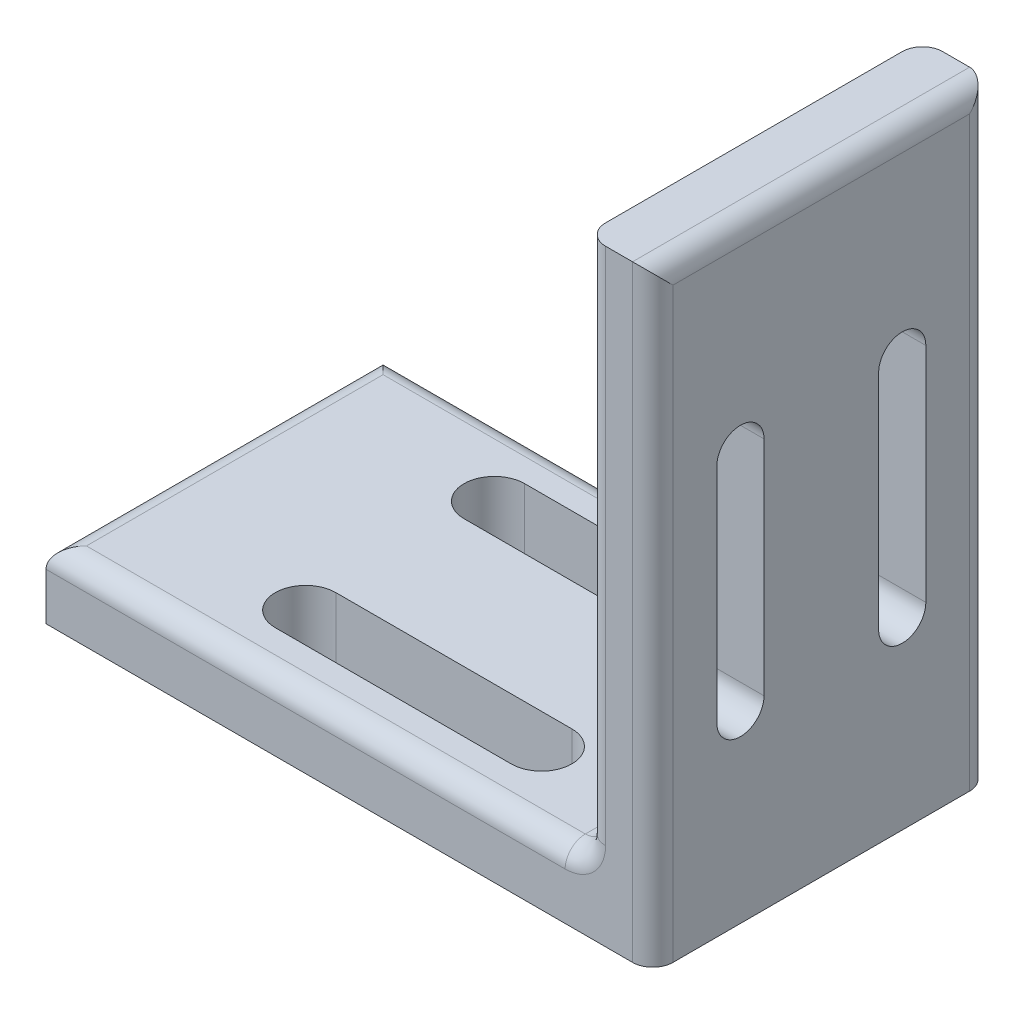
SolidWorks part; units mm, degrees
material "ABS"
ref_plane "Front Plane" through (0, 0, 0) normal (0, 0, 1) x (1, 0, 0)
ref_plane "Top Plane" through (0, 0, 0) normal (0, 1, 0) x (1, 0, 0)
ref_plane "Right Plane" through (0, 0, 0) normal (1, 0, 0) x (0, 0, -1)
sketch "Sketch2" plane through (0, 0, 0) normal (0, 1, 0) x (1, 0, 0)
  line L1 (-22.5, 12.5) -> (22.5, 12.5)
  line L2 (-22.5, 12.5) -> (-22.5, -12.5)
  line L3 (-22.5, -12.5) -> (22.5, -12.5)
  line L4 (22.5, 12.5) -> (22.5, -12.5)
  line L5 (-22.5, 12.5) -> (22.5, -12.5) construction
  line L6 (-22.5, -12.5) -> (22.5, 12.5) construction
  point P0 (0, 0)
  dimension "D1" = 45
  dimension "D2" = 25
extrude "Boss-Extrude1" add sketch "Sketch2" along normal blind 5
sketch "Sketch3" plane through (0, 5, 0) normal (0, 1, 0) x (1, 0, 0)
  line L0 (-8.75, 7) -> (8.75, 7) construction
  line L1 (-8.75, 9.25) -> (8.75, 9.25)
  line L2 (-8.75, 4.75) -> (8.75, 4.75)
  line L3 (-8.75, -7) -> (8.75, -7) construction
  line L4 (-8.75, -4.75) -> (8.75, -4.75)
  line L5 (-8.75, -9.25) -> (8.75, -9.25)
  arc A0 (-8.75, 9.25) -> (-8.75, 4.75) centre (-8.75, 7) ccw
  arc A1 (8.75, 4.75) -> (8.75, 9.25) centre (8.75, 7) ccw
  arc A2 (-8.75, -4.75) -> (-8.75, -9.25) centre (-8.75, -7) ccw
  arc A3 (8.75, -9.25) -> (8.75, -4.75) centre (8.75, -7) ccw
  point P2 (0, 7)
  point P7 (0, -7)
  point P14 (-11, 7)
  point P15 (11, 7)
  point P17 (-11, -7)
  point P18 (11, -7)
  dimension "D1" = 22
  dimension "D2" = 4.5
  dimension "D3" = 22
  dimension "D4" = 4.5
  dimension "D5" = 0
  dimension "D6" = 0
  dimension "D7" = 7
  dimension "D8" = 7
extrude "Cut-Extrude1" cut sketch "Sketch3" against normal through all
sketch "Sketch5" plane through (0, 5, 0) normal (0, 1, 0) x (1, 0, 0)
  line L0 (-22.5, -12.5) -> (22.5, -12.5) construction
  line L1 (22.5, 12.5) -> (17.5, 12.5)
  line L2 (22.5, 12.5) -> (22.5, -12.5)
  line L3 (22.5, -12.5) -> (17.5, -12.5)
  line L4 (17.5, 12.5) -> (17.5, -12.5)
  dimension "D1" = 5
extrude "Boss-Extrude2" add sketch "Sketch5" along normal blind 40
sketch "Sketch6" plane through (17.5, 0, 0) normal (-1, 0, 0) x (0, 0, 1)
  line L0 (-6, 30.25) -> (-6, 13.75) construction
  line L1 (-4.25, 30.25) -> (-4.25, 13.75)
  line L2 (-7.75, 30.25) -> (-7.75, 13.75)
  line L3 (6, 30.25) -> (6, 13.75) construction
  line L4 (7.75, 30.25) -> (7.75, 13.75)
  line L5 (4.25, 30.25) -> (4.25, 13.75)
  line L6 (-12.5, 0) -> (12.5, 0) construction
  arc A0 (-4.25, 30.25) -> (-7.75, 30.25) centre (-6, 30.25) ccw
  arc A1 (-7.75, 13.75) -> (-4.25, 13.75) centre (-6, 13.75) ccw
  arc A2 (7.75, 30.25) -> (4.25, 30.25) centre (6, 30.25) ccw
  arc A3 (4.25, 13.75) -> (7.75, 13.75) centre (6, 13.75) ccw
  point P2 (-6, 22)
  point P7 (6, 22)
  point P14 (-6, 32)
  point P15 (-6, 12)
  point P16 (6, 32)
  point P17 (6, 12)
  dimension "D1" = 20
  dimension "D2" = 20
  dimension "D3" = 3.5
  dimension "D4" = 3.5
  dimension "D5" = 6
  dimension "D6" = 6
  dimension "D7" = 22
  dimension "D8" = 22
extrude "Cut-Extrude2" cut sketch "Sketch6" against normal through all
fillet "Fillet2" radius 1.5 9 edges at (-2.5, 5, 12.5) (-22.5, 5, 0) (-2.5, 5, -12.5) (17.5, 5, 0) (22.5, 45, 0) (17.5, 25, 12.5) (17.5, 25, -12.5) (22.5, 22.5, 12.5) (22.5, 22.5, -12.5)
